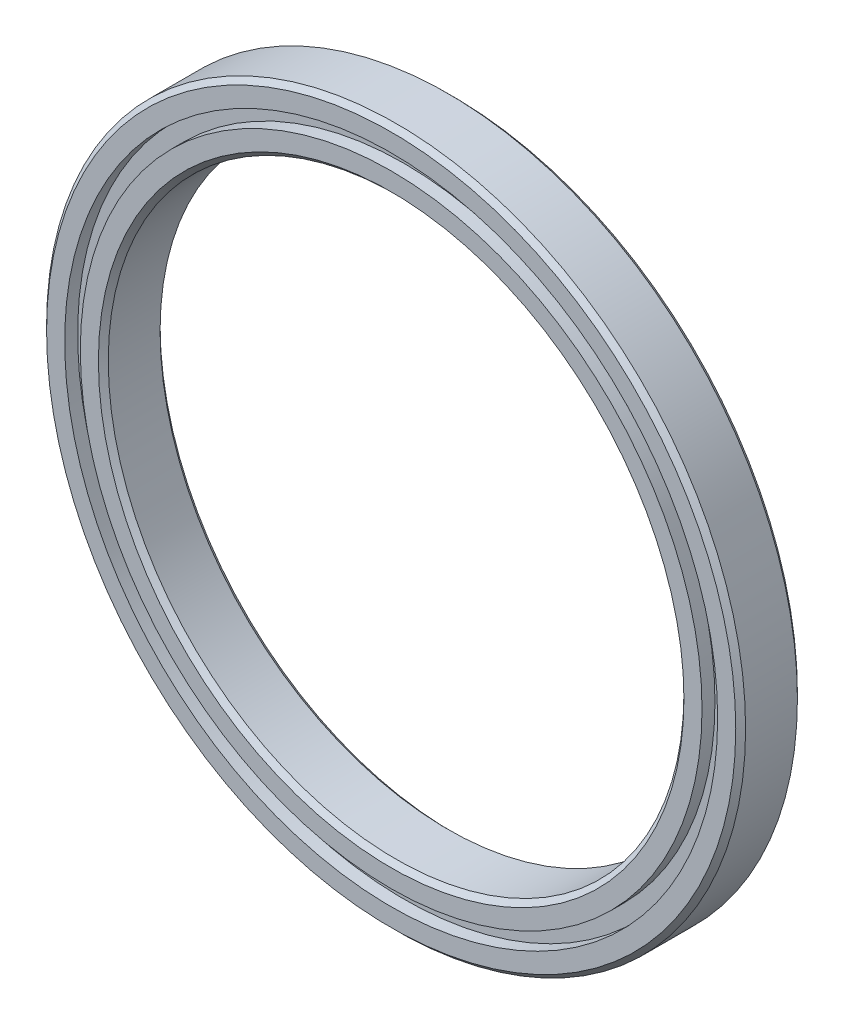
SolidWorks part; units mm, degrees
ref_plane "Front Plane" through (0, 0, 0) normal (0, 0, 1) x (1, 0, 0)
ref_plane "Top Plane" through (0, 0, 0) normal (0, 1, 0) x (1, 0, 0)
ref_plane "Right Plane" through (0, 0, 0) normal (1, 0, 0) x (0, 0, -1)
sketch "Sketch1" plane through (0, 0, 0) normal (0, 0, 1) x (1, 0, 0)
  circle A0 centre (-4.5388, -45.532) radius 22.225
  circle A1 centre (-4.5388, -45.532) radius 26.9875
  dimension "D1" = 44.45
  dimension "D2" = 53.975
extrude "Extrude1" add sketch "Sketch1" along normal blind 4.7625
sketch "Sketch2" plane through (0, 0, 4.7625) normal (0, 0, 1) x (1, 0, 0)
  circle A0 centre (-4.5388, -45.532) radius 24.003
  circle A1 centre (-4.5388, -45.532) radius 22.225 construction
  circle A2 centre (-4.5388, -45.532) radius 25.2095
  dimension "D1" = 48.006
  dimension "D2" = 50.419
extrude "Cut-Extrude1" cut sketch "Sketch2" against normal blind 1
sketch "Sketch3" plane through (0, 0, 0) normal (0, 0, -1) x (-1, 0, 0)
  circle A1 centre (4.5388, -45.532) radius 25.2095
  circle A2 centre (4.5388, -45.532) radius 25.2095
  circle A3 centre (4.5388, -45.532) radius 24.003
  circle A4 centre (4.5388, -45.532) radius 24.003
  dimension "D1" = 0
  dimension "D2" = 0
extrude "Cut-Extrude2" cut sketch "Sketch3" against normal blind 1
chamfer "Chamfer1" distance 0.381 angle 45 4 edges at (17.6862, -45.532, 0) (22.4487, -45.532, 0) (17.6862, -45.532, 4.7625) (22.4487, -45.532, 4.7625)
